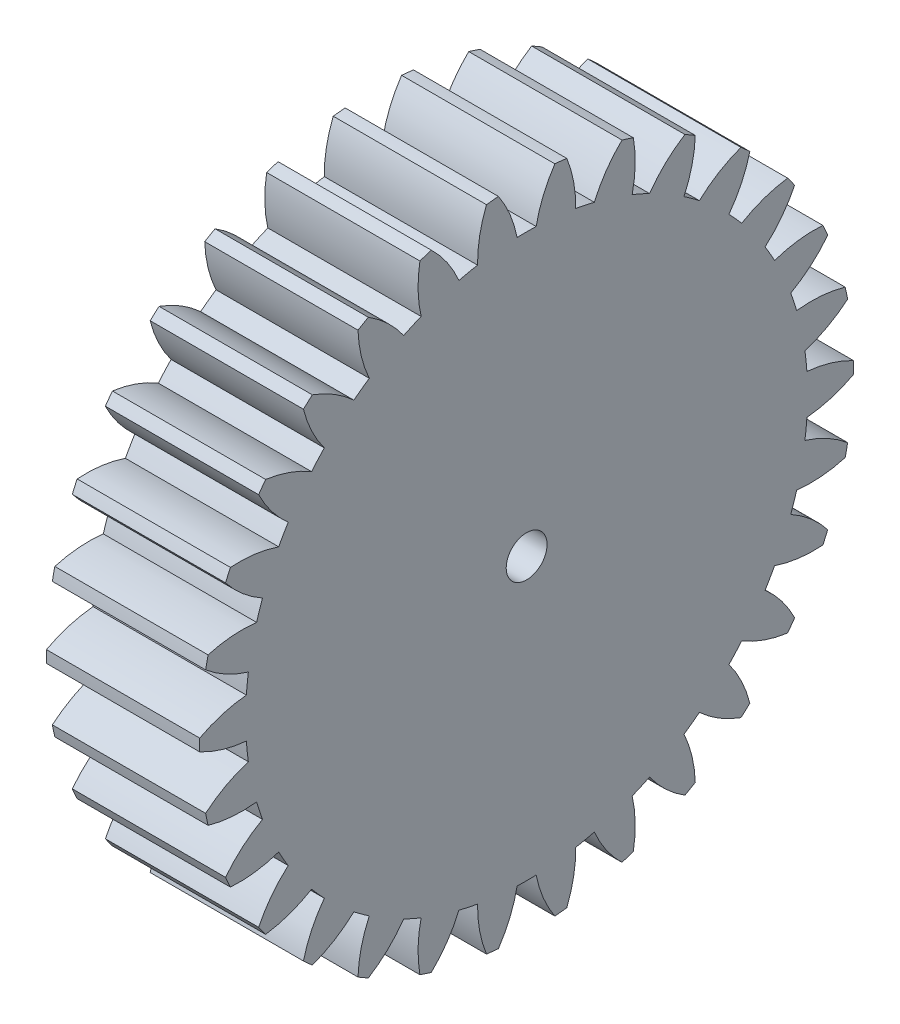
SolidWorks part; units mm, degrees
ref_plane "Plane1" through (0, 0, 0) normal (0, 0, 1) x (1, 0, 0)
ref_plane "Plane2" through (0, 0, 0) normal (0, 1, 0) x (1, 0, 0)
ref_plane "Plane3" through (0, 0, 0) normal (1, 0, 0) x (0, 0, -1)
other "Configuration Table"
sketch "HoldingSke" plane through (0, 0, 0) normal (0, 1, 0) x (1, 0, 0)
  line L0 (0, 0) -> (0.866, -0.5)
  line L1 (-15, 0) -> (100, 0) construction
  line L2 (0, 0) -> (-2.1039, 2.3779)
  line L3 (0, 0) -> (-11.863, 4.5341)
  line L4 (0, 0) -> (7.479, 4.318)
  line L5 (0, 0) -> (-46.8476, -17.4728)
  line L6 (0, 0) -> (-6.2172, -4.1948)
  line L7 (-2.1039, 2.3779) -> (8.6586, 51.2059)
  line L8 (-76.2, 54.61) -> (-75.9, 54.61)
  line L9 (-71.009, 38.7566) -> (-53.1078, 45.2721)
  line L10 (-76.2, 71.12) -> (104.1128, 71.12)
  line L11 (0, 0) -> (-7.5, 0)
  line L12 (-76.2, 101.6) -> (-76.162, 101.6)
  line L13 (24.9733, 27.94) -> (52.9518, 28.4284)
  line L14 (24.9733, 27.94) -> (24.9743, 27.94)
  line L15 (24.9733, 27.94) -> (100.4006, 29.5858)
  line L16 (-63.627, -1) -> (-12.827, -1)
  circle A0 centre (0, 0) radius 1
  circle A1 centre (0, 0) radius 13.749
  circle A2 centre (0, 0) radius 37.5
  circle A3 centre (0, 0) radius 1
  dimension "Hub_dia" = 75
  dimension "Pitch" = 1
  dimension "Overall_len" = 50
  dimension "Thickness" = 7.5
  dimension "OAL" = 50.0001
  dimension "Ap" = 20
  dimension "H" = 19.05
  dimension "Pitch_radius" = 180.3128
  dimension "Width" = 7.5
  dimension "Backlash" = 0.038
  dimension "Addendum_fac" = 1
  dimension "Dedendum_fac" = 1.25
  dimension "Clearance_fac" = 0.25
  dimension "Dedendum_add" = 0.001
  dimension "Module" = 1
sketch "BasProSke" plane through (0, 0, 0) normal (0, 1, 0) x (1, 0, 0)
  line L0 (-10, 0) -> (60, 0) construction
  line L1 (0, 0) -> (0, 16)
  line L2 (0, 0) -> (7.5, 0)
  line L3 (7.5, 0) -> (7.5, 16)
  line L4 (7.5, 16) -> (0, 16)
  dimension "Thickness" = 7.5
revolve "Base-Revolve" add sketch "BasProSke" angle 360 about L0
sketch "TooCutSke" plane through (0, 0, 0) normal (1, 0, 0) x (0, 0, -1)
  line L1 (0, 0) -> (0, 107) construction
  line L2 (0, 0) -> (-0.8515, 14.9758) construction
  line L3 (0, 0) -> (-3.1323, 29.8014) construction
  line L4 (-0.8515, 14.9758) -> (-1.5661, 14.9007) construction
  arc A0 (0.4664, 13.7411) -> (-0.4664, 13.7411) centre (0, 0) ccw
  arc A1 (1.3975, 15.9644) -> (-1.3975, 15.9644) centre (0, 0) ccw
  circle A2 centre (0, 0) radius 15 construction
  circle A3 centre (0, 0) radius 14.0954 construction
  arc A4 (-0.4664, 13.7411) -> (-1.3975, 15.9644) centre (-6.3534, 12.5823) ccw
  arc A5 (1.3975, 15.9644) -> (0.4664, 13.7411) centre (6.3534, 12.5823) ccw
extrude "ToothCut" cut sketch "TooCutSke" along normal through all
fillet "Breaks" [suppressed] radius 0.02
fillet "RootFillets" [suppressed] radius 0.251
pattern_circular "TeethCuts" count 30 every 12 about axis through (-10, 0, 0) along (1, 0, 0) of "ToothCut", "RootFillets", "Breaks"
sketch "HubNeaOneSke" plane through (0, 0, 0) normal (-1, 0, 0) x (0, 0, 1)
  circle A0 centre (0, 0) radius 13.749
extrude "HubNearOne" [suppressed] add sketch "HubNeaOneSke" along normal blind 42.5001
sketch "HubNeaBotSke" plane through (0, 0, 0) normal (-1, 0, 0) x (0, 0, 1)
  circle A0 centre (0, 0) radius 13.749
extrude "HubNearBoth" [suppressed] add sketch "HubNeaBotSke" along normal blind 21.25
ref_plane "FarPln" through (7.5, 0, 0) normal (1, 0, 0) x (0, 0, -1)
sketch "HubFarSke" plane through (7.5, 0, 0) normal (1, 0, 0) x (0, 0, -1)
  circle A0 centre (0, 0) radius 13.749
extrude "HubFar" [suppressed] add sketch "HubFarSke" along normal blind 21.25
sketch "BorSke" plane through (0, 0, 0) normal (1, 0, 0) x (0, 0, -1)
  circle A0 centre (0, 0) radius 1
extrude "Bore" cut sketch "BorSke" along normal mid plane 100.0001
sketch "KeySke" plane through (0, 0, 0) normal (1, 0, 0) x (0, 0, -1)
  line L0 (-0.4, 0) -> (-0.4, 1.3)
  line L1 (-0.4, 1.3) -> (0.4, 1.3)
  line L2 (0.4, 1.3) -> (0.4, 0)
  line L3 (0, 0) -> (0, 34) construction
  line L4 (-0.4, 0) -> (0.4, 0)
extrude "Keyway" [suppressed] cut sketch "KeySke" along normal mid plane 100.0001
pattern_circular "Keyway2" [suppressed] count 2 every 90 about axis through (-10, 0, 0) along (1, 0, 0)
equation "' \"Module@HoldingSke\" = 6.35"
equation "' \"Num_teeth@HoldingSke\" = 12"
equation "' \"Ap@HoldingSke\" =  20"
equation "' \"Ap@HoldingSke\" = 20"
equation "' \"Width@HoldingSke\" = 0.5 * 25.4"
equation "' \"Hub_dia@HoldingSke\"= 1 * 25.4"
equation "' \"Hub_dia@HoldingSke\" = 1 * 25.4"
equation "' \"Overall_len@HoldingSke\" = 1.0 * 25.4"
equation "' \"Bore@HoldingSke\" = 0.75 * 25.4"
equation "' \"T_dim@HoldingSke\" = 0.1 * 25.4"
equation "' \"Width@KeySke\" = 0.25 * 25.4"
equation "' \"Show_teeth@HoldingSke\" = 13"
equation "' \"Backlash@HoldingSke\" = 0.009 * 25.4"
equation "' \"Addendum_fac@HoldingSke\" = 1.0"
equation "' \"Dedendum_fac@HoldingSke\" = 1.25"
equation "' \"Dedendum_add@HoldingSke\" = 0.00005 * 25.4"
equation "' \"Clearance_fac@HoldingSke\" = 0.25"
equation "\"Pitch@HoldingSke\" = 1 / \"Module@HoldingSke\""
equation "\"Overcut_dia@TooCutSke\" = (\"Num_teeth@HoldingSke\" + 2 * \"Addendum_fac@HoldingSke\") / \"Pitch@HoldingSke\" + 0.002 * 25.4"
equation "\"Pitch_dia@TooCutSke\" = \"Num_teeth@HoldingSke\" / \"Pitch@HoldingSke\""
equation "\"Base_dia@TooCutSke\" = \"Num_teeth@HoldingSke\" / \"Pitch@HoldingSke\" * cos((\"Ap@HoldingSke\"  * 3.14159265 / 180))"
equation "\"Root_dia@TooCutSke\" = (\"Num_teeth@HoldingSke\" + 2) / \"Pitch@HoldingSke\" - 2 * (\"Addendum_fac@HoldingSke\" + \"Dedendum_fac@HoldingSke\") / \"Pitch@HoldingSke\" - \"Dedendum_add@HoldingSke\" * 2"
equation "\"Half_ang@TooCutSke\" = 180 / \"Num_teeth@HoldingSke\""
equation "\"Half_CT@TooCutSke\" = \"Num_teeth@HoldingSke\" / \"Pitch@HoldingSke\" * sin((3.14159265 / 2 / \"Num_teeth@HoldingSke\")) / 2 - 7 * \"Backlash@HoldingSke\" / 4"
equation "\"Flank_rad@TooCutSke\" = \"Num_teeth@HoldingSke\" / \"Pitch@HoldingSke\" / 5"
equation "\"Radius@RootFillets\" = \"Clearance_fac@HoldingSke\" / \"Pitch@HoldingSke\" + \"Dedendum_add@HoldingSke\""
equation "\"Break_rad@Breaks\" = 0.02 / \"Pitch@HoldingSke\""
equation "\"Thickness@HoldingSke\" = \"Width@HoldingSke\""
equation "\"OAL@HoldingSke\" = \"Thickness@HoldingSke\""
equation "\"MHD@HoldingSke\" = (\"Num_teeth@HoldingSke\" + 2) / \"Pitch@HoldingSke\" - 2 * (\"Addendum_fac@HoldingSke\" + \"Dedendum_fac@HoldingSke\")  / \"Pitch@HoldingSke\" - \"Dedendum_add@HoldingSke\" * 2"
equation "\"MBD@HoldingSke\" = (\"Num_teeth@HoldingSke\" + 2) / \"Pitch@HoldingSke\" - 2 * (\"Addendum_fac@HoldingSke\" + \"Dedendum_fac@HoldingSke\")  / \"Pitch@HoldingSke\" - \"Dedendum_add@HoldingSke\" * 2 - 0.002 * 25.4"
equation "\"MHD@HoldingSke\" = ((sgn( \"MHD@HoldingSke\" - \"Hub_dia@HoldingSke\" )-1)*( \"MHD@HoldingSke\" - \"Hub_dia@HoldingSke\" ))/-2+ \"Hub_dia@HoldingSke\""
equation "\"MBD@HoldingSke\" = ((sgn( \"MBD@HoldingSke\" - \"Bore@HoldingSke\" )-1)*( \"MBD@HoldingSke\" - \"Bore@HoldingSke\" ))/-2+ \"Bore@HoldingSke\""
equation "\"OAL@HoldingSke\" = ((sgn( \"OAL@HoldingSke\" - \"Overall_len@HoldingSke\" )+1)*( \"OAL@HoldingSke\" - \"Overall_len@HoldingSke\" ))/2 + \"Overall_len@HoldingSke\" + 0.000002 * 25.4"
equation "\"Num_teeth@TeethCuts\" = int( \"Show_teeth@HoldingSke\" ) + 1"
equation "\"Num_teeth@TeethCuts\" = ((sgn( \"Num_teeth@TeethCuts\" - \"Num_teeth@HoldingSke\" )-1)*( \"Num_teeth@TeethCuts\" - \"Num_teeth@HoldingSke\" ))/-2+ \"Num_teeth@HoldingSke\""
equation "\"Num_teeth@TeethCuts\" = ((sgn( \"Num_teeth@TeethCuts\" - 2.0)+1)*( \"Num_teeth@TeethCuts\" - 2.0))/2 +2.0"
equation "\"Angle@TeethCuts\" = 360.0 / \"Num_teeth@HoldingSke\""
equation "\"Diameter@BasProSke\" = (\"Num_teeth@HoldingSke\" + 2 * \"Addendum_fac@HoldingSke\") / \"Pitch@HoldingSke\""
equation "\"Thickness@BasProSke\"  = \"Thickness@HoldingSke\""
equation "' \"Fillet_rad@BasProSke\" =  \"Thickness@HoldingSke\" * 0.05"
equation "' \"Fillet_rad@BasProSke\" = \"Thickness@HoldingSke\" * 0.05"
equation "\"MHD@HoldingSke\" = ((sgn( \"MHD@HoldingSke\" - \"Root_dia@TooCutSke\" )-1)*( \"MHD@HoldingSke\" - \"Root_dia@TooCutSke\" ))/-2+ \"Root_dia@TooCutSke\""
equation "\"Diameter@HubNeaOneSke\" = \"MHD@HoldingSke\""
equation "\"Length@HubNearOne\" = \"OAL@HoldingSke\" - \"Thickness@BasProSke\""
equation "\"Diameter@HubNeaBotSke\" = \"MHD@HoldingSke\""
equation "\"Length@HubNearBoth\" = ( \"OAL@HoldingSke\" - \"Thickness@BasProSke\" ) / 2.0"
equation "\"Thickness@FarPln\" = \"Thickness@BasProSke\""
equation "\"Diameter@HubFarSke\" = \"MHD@HoldingSke\""
equation "\"Length@HubFar\" = ( \"OAL@HoldingSke\" - \"Thickness@BasProSke\" ) / 2.0"
equation "\"Diameter@BorSke\" = \"MBD@HoldingSke\""
equation "\"D1@Bore\" = \"OAL@HoldingSke\" * 2.0"
equation "\"D1@Keyway\" = \"OAL@HoldingSke\" * 2.0"
equation "\"Offset@KeySke\" = \"T_dim@HoldingSke\" + \"MBD@HoldingSke\" / 2.0"
